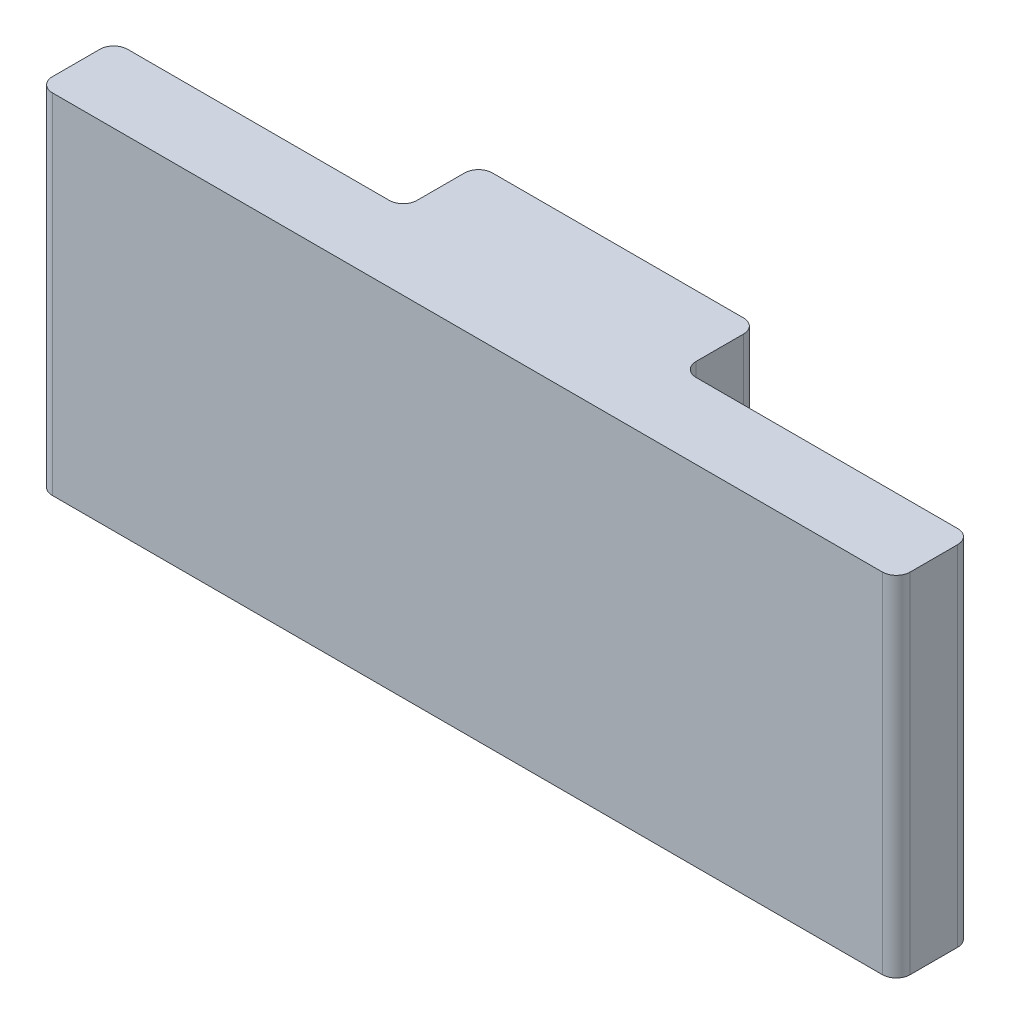
SolidWorks part; units mm, degrees
ref_plane "前视基准面" through (0, 0, 0) normal (0, 0, 1) x (1, 0, 0)
ref_plane "上视基准面" through (0, 0, 0) normal (0, 1, 0) x (1, 0, 0)
ref_plane "右视基准面" through (0, 0, 0) normal (1, 0, 0) x (0, 0, -1)
sketch "草图1" plane through (0, 0, 0) normal (0, 1, 0) x (1, 0, 0)
  line L0 (-297.5, 0) -> (297.5, 0)
  line L1 (0, 108) -> (0, -23.5507) construction
  line L2 (307.5, 10) -> (307.5, 44)
  line L3 (-90, 108) -> (90, 108)
  line L4 (100, 98) -> (100, 64)
  line L5 (110, 54) -> (297.5, 54)
  line L6 (-307.5, 10) -> (-307.5, 44)
  line L7 (-110, 54) -> (-297.5, 54)
  line L8 (-100, 98) -> (-100, 64)
  arc A0 (297.5, 0) -> (307.5, 10) centre (297.5, 10) ccw
  arc A1 (307.5, 44) -> (297.5, 54) centre (297.5, 44) ccw
  arc A2 (100, 64) -> (110, 54) centre (110, 64) ccw
  arc A3 (90, 108) -> (100, 98) centre (90, 98) cw
  arc A4 (-297.5, 0) -> (-307.5, 10) centre (-297.5, 10) cw
  arc A5 (-307.5, 44) -> (-297.5, 54) centre (-297.5, 44) cw
  arc A6 (-100, 64) -> (-110, 54) centre (-110, 64) cw
  arc A7 (-90, 108) -> (-100, 98) centre (-90, 98) ccw
  point P9 (307.5, 0)
  point P13 (307.5, 54)
  point P18 (100, 108)
  point P22 (0, 0)
  dimension "D5" = 10
  dimension "D1" = 307.5
  dimension "D2" = 54
  dimension "D3" = 100
  dimension "D4" = 108
  dimension "D6" = 595
  dimension "D7" = 615
extrude "凸台-拉伸1" add sketch "草图1" along normal blind 250
